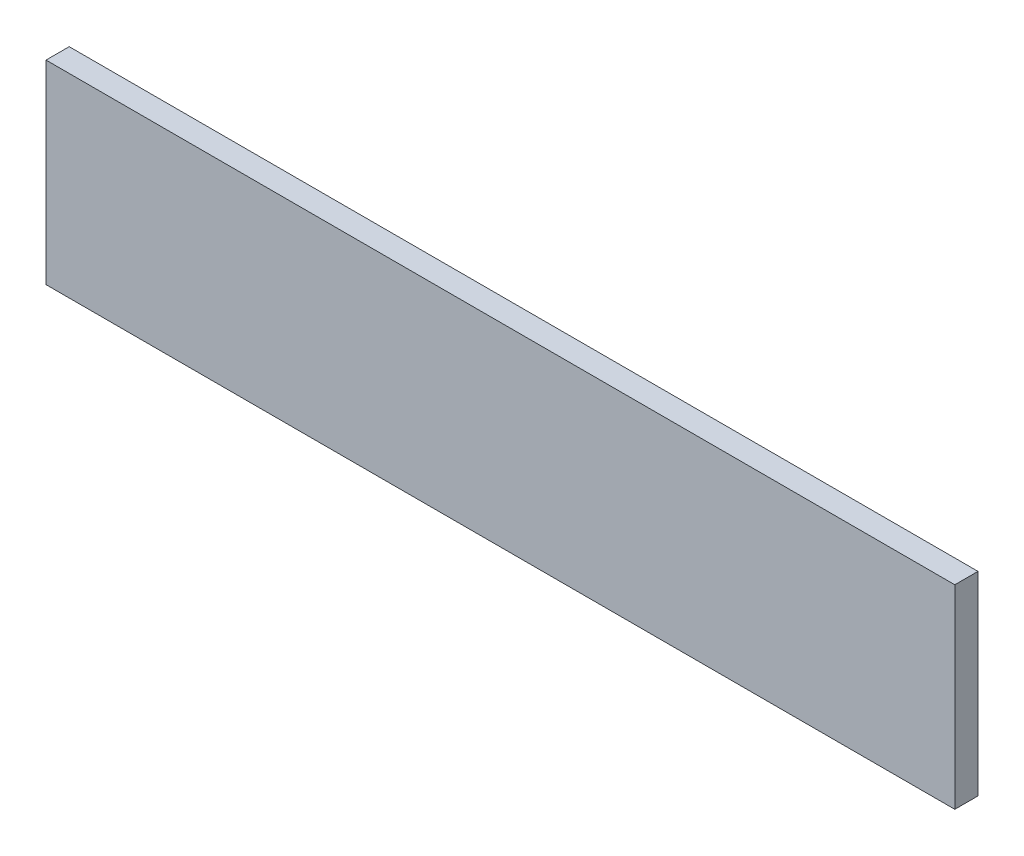
SolidWorks part; units mm, degrees
other "COLL.BOX-Estrusione-Estrusione2"
ref_plane "Piano frontale" through (0, 0, 0) normal (0, 0, 1) x (1, 0, 0)
ref_plane "Piano superiore" through (0, 0, 0) normal (0, 1, 0) x (1, 0, 0)
ref_plane "Piano destro" through (0, 0, 0) normal (1, 0, 0) x (0, 0, -1)
sketch "Schizzo1" plane through (0, 0, 0) normal (0, 0, 1) x (1, 0, 0)
  line L1 (-1000, 200) -> (1000, 200)
  line L2 (-1000, 200) -> (-1000, -200)
  line L3 (-1000, -200) -> (1000, -200)
  line L4 (1000, 200) -> (1000, -200)
  line L5 (-1000, 200) -> (1000, -200) construction
  line L6 (-1000, -200) -> (1000, 200) construction
  point P0 (0, 0)
  dimension "D1" = 400
  dimension "D2" = 2000
extrude "Estrusione-Estrusione1" add sketch "Schizzo1" along normal blind 40
sketch "Schizzo2" plane through (0, 0, 0) normal (0, 0, -1) x (-1, 0, 0)
  line L1 (1018.6288, -217.9946) -> (-1018.6288, -217.9946)
  line L2 (1018.6288, -217.9946) -> (1018.6288, 217.9946)
  line L3 (1018.6288, 217.9946) -> (-1018.6288, 217.9946)
  line L4 (-1018.6288, -217.9946) -> (-1018.6288, 217.9946)
  line L5 (1018.6288, -217.9946) -> (-1018.6288, 217.9946) construction
  line L6 (1018.6288, 217.9946) -> (-1018.6288, -217.9946) construction
  point P0 (0, 0)
extrude "Estrusione-Estrusione2" add sketch "Schizzo2" against normal blind 52 separate body
